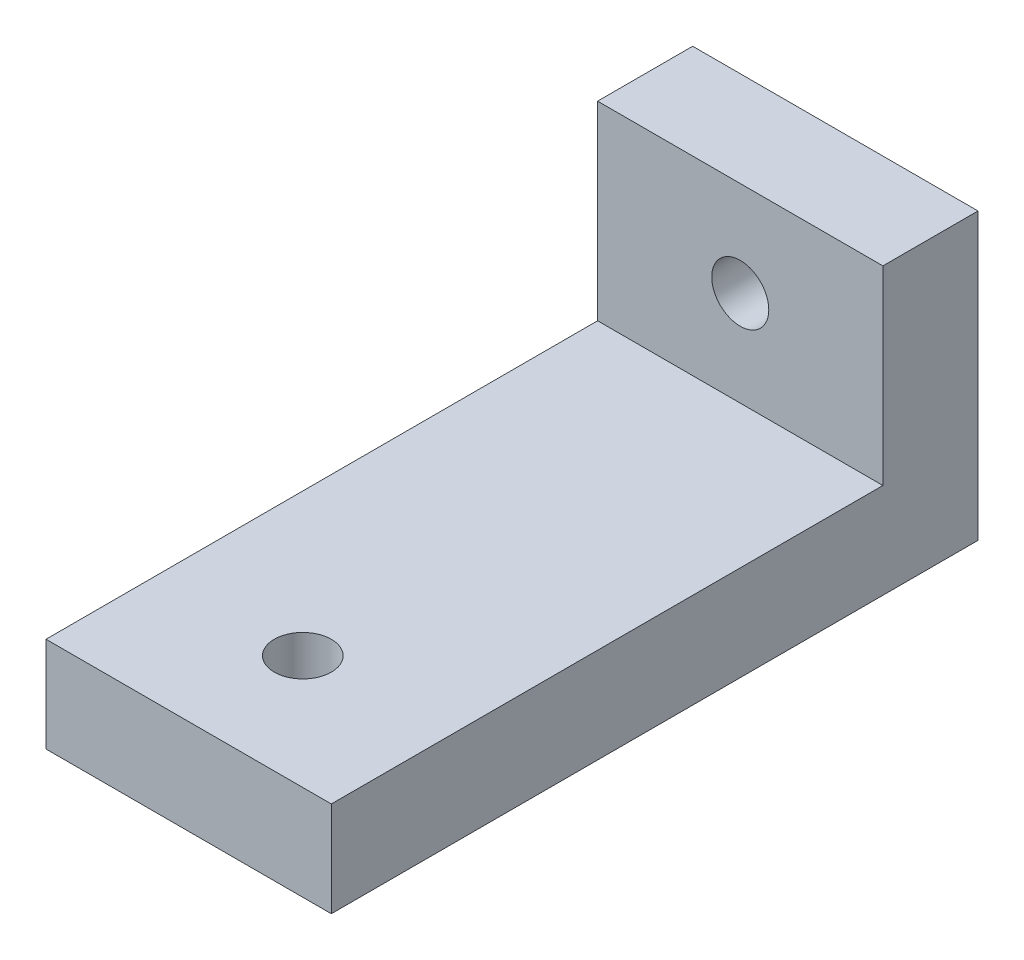
SolidWorks part; units mm, degrees
ref_plane "前视基准面" through (0, 0, 0) normal (0, 0, 1) x (1, 0, 0)
ref_plane "上视基准面" through (0, 0, 0) normal (0, 1, 0) x (1, 0, 0)
ref_plane "右视基准面" through (0, 0, 0) normal (1, 0, 0) x (0, 0, -1)
sketch "Sketch1" plane through (0, 0, 0) normal (0, 1, 0) x (1, 0, 0)
  line L1 (-7.5, 17.25) -> (7.5, 17.25)
  line L2 (-7.5, 17.25) -> (-7.5, -17.25)
  line L3 (-7.5, -17.25) -> (7.5, -17.25)
  line L4 (7.5, 17.25) -> (7.5, -17.25)
  line L5 (-7.5, 17.25) -> (7.5, -17.25) construction
  line L6 (-7.5, -17.25) -> (7.5, 17.25) construction
  point P0 (0, 0)
extrude "Extrude1" add sketch "Sketch1" along normal blind 5
sketch "Sketch2" plane through (0, 5, 0) normal (0, 1, 0) x (1, 0, 0)
  line L0 (7.5, -17.25) -> (7.5, 17.25) construction
  line L1 (-7.5, 17.25) -> (7.5, 17.25)
  line L2 (-7.5, 17.25) -> (-7.5, 12.25)
  line L3 (-7.5, 12.25) -> (7.5, 12.25)
  line L4 (7.5, 17.25) -> (7.5, 12.25)
extrude "Extrude2" add sketch "Sketch2" along normal blind 10
sketch "Sketch3" plane through (0, 5, 0) normal (0, 1, 0) x (1, 0, 0)
  circle A0 centre (0, -11.25) radius 1.5
extrude "Extrude3" cut sketch "Sketch3" against normal blind 10
sketch "Sketch4" plane through (0, 0, -12.25) normal (0, 0, 1) x (1, 0, 0)
  circle A0 centre (0, 10) radius 1.5
extrude "Extrude4" cut sketch "Sketch4" against normal blind 10
sketch "Sketch5" plane through (0, 0, -17.25) normal (0, 0, -1) x (-1, 0, 0)
  line L4 (-7.5, 0) -> (7.5, 0)
  line L5 (7.5, 0) -> (7.5, 15)
  line L6 (7.5, 15) -> (-7.5, 15)
  line L7 (-7.5, 15) -> (-7.5, 0)
  line L8 (-7.5, 0) -> (7.5, 0)
  line L9 (7.5, 0) -> (7.5, 15)
  line L10 (7.5, 15) -> (-7.5, 15)
  line L11 (-7.5, 15) -> (-7.5, 0)
  dimension "D1" = 0
extrude "Extrude5" cut sketch "Sketch5" against normal blind 0.5
sketch "Sketch6" plane through (0, 0, -12.25) normal (0, 0, 1) x (1, 0, 0)
  line L4 (-7.5, 5) -> (7.5, 5)
  line L5 (7.5, 5) -> (7.5, 15)
  line L6 (7.5, 15) -> (-7.5, 15)
  line L7 (-7.5, 15) -> (-7.5, 5)
  line L8 (-7.5, 5) -> (7.5, 5)
  line L9 (7.5, 5) -> (7.5, 15)
  line L10 (7.5, 15) -> (-7.5, 15)
  line L11 (-7.5, 15) -> (-7.5, 5)
  circle A0 centre (0, 10) radius 1.5 construction
  circle A1 centre (0, 10) radius 1.5
  dimension "D1" = 0
extrude "Extrude6" add sketch "Sketch6" along normal blind 0.5
